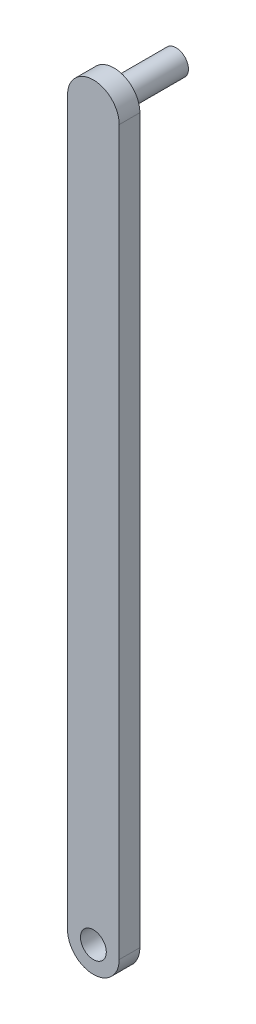
SolidWorks part; units mm, degrees
ref_plane "Front Plane" through (0, 0, 0) normal (0, 0, 1) x (1, 0, 0)
ref_plane "Top Plane" through (0, 0, 0) normal (0, 1, 0) x (1, 0, 0)
ref_plane "Right Plane" through (0, 0, 0) normal (1, 0, 0) x (0, 0, -1)
sketch "Sketch1" plane through (0, 0, 0) normal (0, 0, 1) x (1, 0, 0)
  line L0 (-3.175, 0) -> (-3.175, -88.9)
  line L1 (3.175, 0) -> (3.175, -88.9)
  arc A0 (3.175, 0) -> (-3.175, 0) centre (0, 0) ccw
  arc A1 (3.175, -88.9) -> (-3.175, -88.9) centre (0, -88.9) cw
  circle A2 centre (0, 0) radius 1.5875
  circle A3 centre (0, -88.9) radius 1.5875
  dimension "D3" = 3.175
  dimension "D4" = 3.175
  dimension "D5" = 3.175
  dimension "D1" = 3.175
  dimension "D2" = 88.9
extrude "Boss-Extrude1" add sketch "Sketch1" along normal blind 2.54
sketch "Sketch2" plane through (0, 0, 2.54) normal (0, 0, 1) x (1, 0, 0)
  circle A0 centre (0, 0) radius 1.524
  dimension "D1" = 3.048
extrude "Boss-Extrude2" add sketch "Sketch2" against normal blind 7.62 from surface at -2.54 starting at face at (0, -44.45, 0)
sketch "Sketch3" plane through (0, 0, 0) normal (0, 0, 1) x (1, 0, 0)
  circle A0 centre (0, 0) radius 1.5875
  dimension "D1" = 3.175
extrude "Boss-Extrude3" add sketch "Sketch3" along normal blind 2.54
